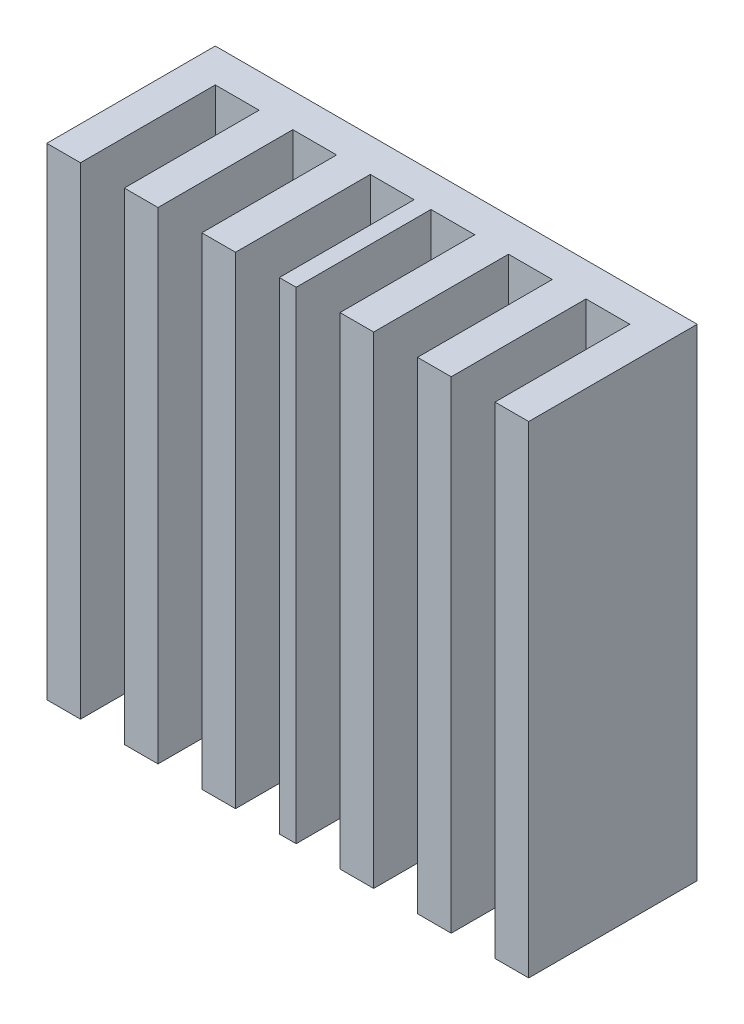
SolidWorks part; units mm, degrees
ref_plane "Plan de face" through (0, 0, 0) normal (0, 0, 1) x (1, 0, 0)
ref_plane "Plan de dessus" through (0, 0, 0) normal (0, 1, 0) x (1, 0, 0)
ref_plane "Plan de droite" through (0, 0, 0) normal (1, 0, 0) x (0, 0, -1)
sketch "Esquisse1" plane through (0, 0, 0) normal (0, 0, 1) x (1, 0, 0)
  line L1 (0, 0) -> (14.3, 0)
  line L2 (0, 0) -> (0, 14.3)
  line L3 (0, 14.3) -> (14.3, 14.3)
  line L4 (14.3, 0) -> (14.3, 14.3)
  dimension "D1" = 14.3
  dimension "D2" = 14.3
extrude "Boss.-Extru.1" add sketch "Esquisse1" along normal blind 5
sketch "Esquisse2" plane through (0, 0, 5) normal (0, 0, 1) x (1, 0, 0)
  line L0 (14.3, 14.3) -> (0, 14.3) construction
  line L1 (0, 14.3) -> (0, 0) construction
  line L2 (1, 14.3) -> (2.3, 14.3)
  line L3 (1, 14.3) -> (1, 0)
  line L4 (1, 0) -> (2.3, 0)
  line L5 (0, 0) -> (14.3, 0) construction
  line L7 (7.15, 14.3) -> (7.15, 0) construction
  line L8 (2.3, 14.3) -> (2.3, 0)
  line L9 (7.4, 14.3) -> (7.4, 0)
  line L10 (3.3, 14.3) -> (4.6, 14.3)
  line L11 (3.3, 14.3) -> (3.3, 0)
  line L12 (3.3, 0) -> (4.6, 0)
  line L13 (4.6, 14.3) -> (4.6, 0)
  line L14 (5.6, 14.3) -> (6.9, 14.3)
  line L15 (5.6, 14.3) -> (5.6, 0)
  line L16 (5.6, 0) -> (6.9, 0)
  line L17 (6.9, 14.3) -> (6.9, 0)
  line L18 (8.7, 0) -> (7.4, 0)
  line L19 (8.7, 14.3) -> (8.7, 0)
  line L20 (8.7, 14.3) -> (7.4, 14.3)
  line L21 (9.7, 14.3) -> (9.7, 0)
  line L22 (11, 0) -> (9.7, 0)
  line L23 (11, 14.3) -> (11, 0)
  line L24 (11, 14.3) -> (9.7, 14.3)
  line L25 (12, 14.3) -> (12, 0)
  line L26 (13.3, 0) -> (12, 0)
  line L27 (13.3, 14.3) -> (13.3, 0)
  line L28 (13.3, 14.3) -> (12, 14.3)
  dimension "D1" = 1
  dimension "D2" = 1.3
  dimension "D3" = 1
  dimension "D4" = 1.3
  dimension "D5" = 1
  dimension "D6" = 1.3
extrude "Enlèv. mat.-Extru.1" cut sketch "Esquisse2" against normal blind 4
sketch "Esquisse3" [suppressed] plane through (0, 0, 5) normal (0, 0, 1) x (1, 0, 0)
  line L0 (3.3, 14.3) -> (2.3, 14.3) construction
  line L1 (-0.39, 13.3) -> (14.7304, 13.3)
  line L2 (-0.39, 13.3) -> (-0.39, 12)
  line L3 (-0.39, 12) -> (14.7304, 12)
  line L4 (14.7304, 13.3) -> (14.7304, 12)
  line L5 (-0.39, 11) -> (14.7304, 11)
  line L6 (-0.39, 11) -> (-0.39, 9.7)
  line L7 (-0.39, 9.7) -> (14.7304, 9.7)
  line L8 (14.7304, 11) -> (14.7304, 9.7)
  line L9 (0, 7.15) -> (14.3, 7.15) construction
  line L10 (0, 14.3) -> (0, 0) construction
  line L11 (14.3, 0) -> (14.3, 14.3) construction
  line L12 (14.7304, 5.6) -> (14.7304, 6.9)
  line L13 (-0.39, 8.7) -> (14.7304, 8.7)
  line L14 (-0.39, 8.7) -> (-0.39, 7.4)
  line L15 (-0.39, 7.4) -> (14.7304, 7.4)
  line L16 (14.7304, 8.7) -> (14.7304, 7.4)
  line L17 (-0.39, 6.9) -> (14.7304, 6.9)
  line L18 (-0.39, 5.6) -> (-0.39, 6.9)
  line L19 (-0.39, 5.6) -> (14.7304, 5.6)
  line L20 (14.7304, 3.3) -> (14.7304, 4.6)
  line L21 (-0.39, 4.6) -> (14.7304, 4.6)
  line L22 (-0.39, 3.3) -> (-0.39, 4.6)
  line L23 (-0.39, 3.3) -> (14.7304, 3.3)
  line L24 (14.7304, 1) -> (14.7304, 2.3)
  line L25 (-0.39, 2.3) -> (14.7304, 2.3)
  line L26 (-0.39, 1) -> (-0.39, 2.3)
  line L27 (-0.39, 1) -> (14.7304, 1)
  dimension "D1" = 1
  dimension "D2" = 1.3
  dimension "D3" = 1
  dimension "D4" = 1.3
  dimension "D5" = 1
  dimension "D6" = 1.3
extrude "Enlèv. mat.-Extru.2" [suppressed] cut sketch "Esquisse3" against normal blind 4
